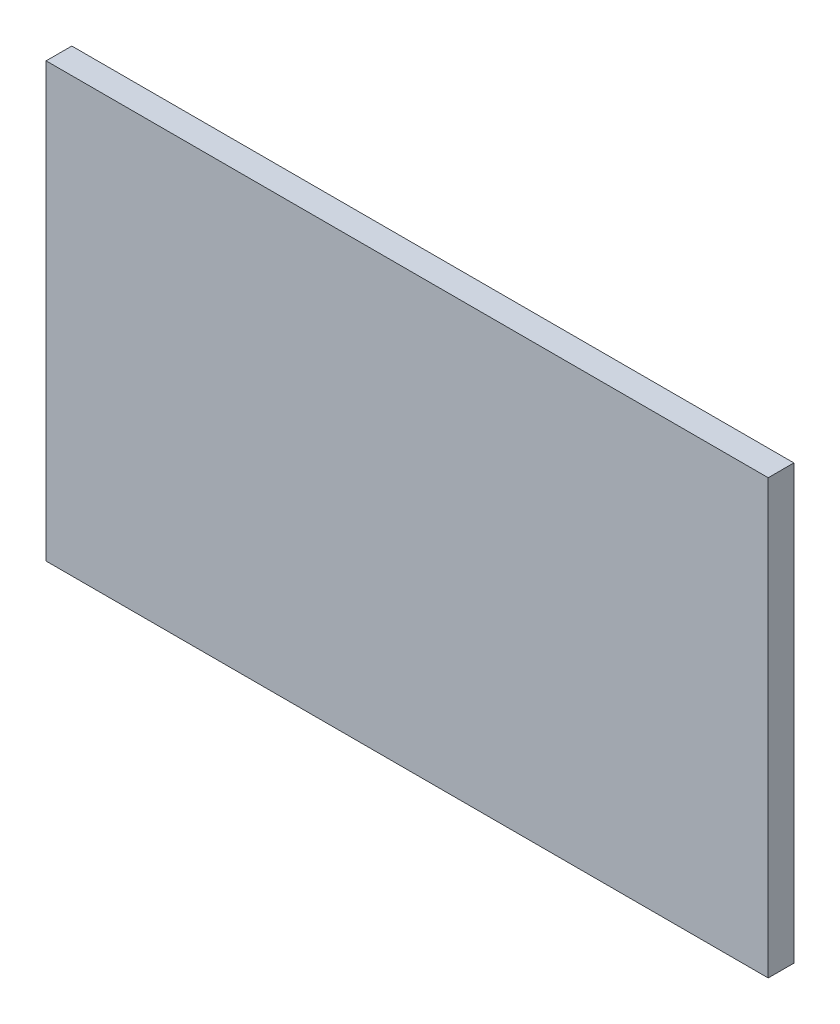
SolidWorks part; units mm, degrees
material "Q235A"
ref_plane "前视" through (0, 0, 0) normal (0, 0, 1) x (1, 0, 0)
ref_plane "上视" through (0, 0, 0) normal (0, 1, 0) x (1, 0, 0)
ref_plane "右视" through (0, 0, 0) normal (1, 0, 0) x (0, 0, -1)
sketch "草图1" plane through (0, 0, 0) normal (0, 0, 1) x (1, 0, 0)
  line L1 (225, -135) -> (-225, -135)
  line L2 (225, -135) -> (225, 135)
  line L3 (225, 135) -> (-225, 135)
  line L4 (-225, -135) -> (-225, 135)
  line L5 (225, -135) -> (-225, 135) construction
  line L6 (225, 135) -> (-225, -135) construction
  point P0 (0, 0)
  dimension "D1" = 270
  dimension "D2" = 450
extrude "凸台-拉伸1" add sketch "草图1" along normal blind 16
